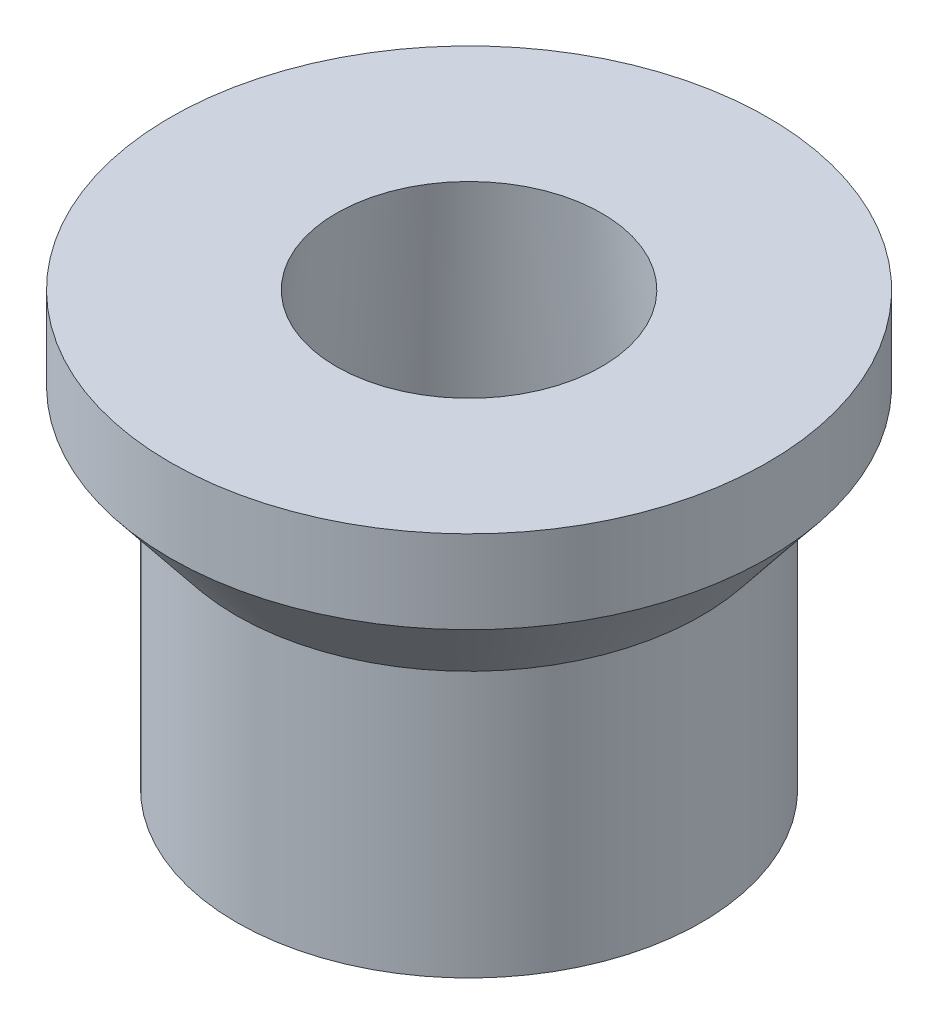
SolidWorks part; units mm, degrees
ref_plane "Front Plane" through (0, 0, 0) normal (0, 0, 1) x (1, 0, 0)
ref_plane "Top Plane" through (0, 0, 0) normal (0, 1, 0) x (1, 0, 0)
ref_plane "Right Plane" through (0, 0, 0) normal (1, 0, 0) x (0, 0, -1)
sketch "Sketch1" plane through (0, 0, 0) normal (0, 0, 1) x (1, 0, 0)
  line L0 (5, 0) -> (7, 0)
  line L1 (7, 0) -> (7, 8)
  line L2 (7, 8) -> (9, 10.5)
  line L4 (9, 10.5) -> (9, 13)
  line L5 (9, 13) -> (4, 13)
  line L6 (4, 13) -> (5, 0)
  line L7 (0, 0) -> (0, 13.7158) construction
  dimension "D1" = 2
  dimension "D2" = 5
  dimension "D3" = 8
  dimension "D4" = 4
  dimension "D5" = 5
  dimension "D6" = 2.5
  dimension "D7" = 13
revolve "Revolve-Thin7" add sketch "Sketch1" angle 360 about L7 wall 0.0001
